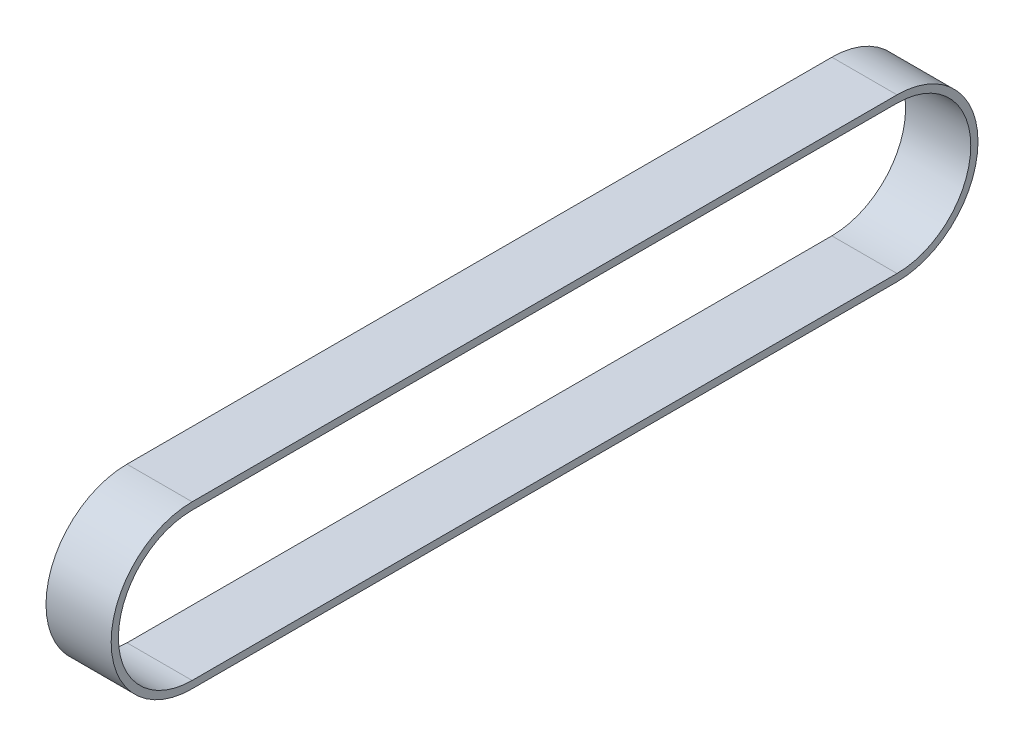
SolidWorks part; units mm, degrees
material "Rubber"
ref_plane "Frente" through (0, 0, 0) normal (0, 0, 1) x (1, 0, 0)
ref_plane "Topo" through (0, 0, 0) normal (0, 1, 0) x (1, 0, 0)
ref_plane "Lateral" through (0, 0, 0) normal (1, 0, 0) x (0, 0, -1)
sketch "Sketch1" plane through (0, 0, 0) normal (1, 0, 0) x (0, 0, -1)
  line L0 (-97.3613, 10.185) -> (0, 10.185)
  line L1 (0, 10.185) -> (0, -10.185) construction
  line L2 (0, -10.185) -> (-97.3613, -10.185)
  line L3 (-97.3613, -10.185) -> (-97.3613, 10.185) construction
  line L4 (-97.3613, 0) -> (0, 0) construction
  arc A0 (0, -10.185) -> (0, 10.185) centre (0, 0) ccw
  arc A1 (-97.3613, 10.185) -> (-97.3613, -10.185) centre (-97.3613, 0) ccw
  dimension "D1" = 10.185
  dimension "D2" = 31.9971
  dimension "D3" = 97.3613
extrude "Extrude-Thin1" add sketch "Sketch1" along normal mid plane 9 thin thin type one direction wall 1
